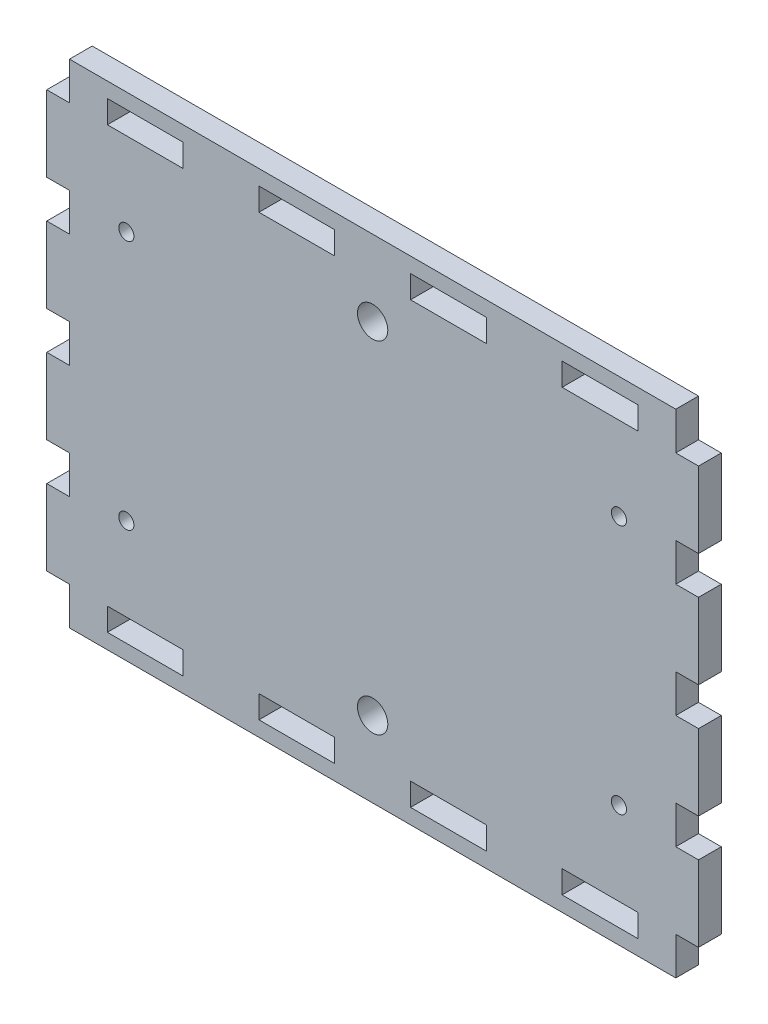
SolidWorks part; units mm, degrees
ref_plane "前视基准面" through (0, 0, 0) normal (0, 0, 1) x (1, 0, 0)
ref_plane "上视基准面" through (0, 0, 0) normal (0, 1, 0) x (1, 0, 0)
ref_plane "右视基准面" through (0, 0, 0) normal (1, 0, 0) x (0, 0, -1)
sketch "草图1" plane through (0, 0, 0) normal (0, 0, 1) x (1, 0, 0)
  line L0 (0, -55) -> (0, 55) construction
  line L1 (-32.5, 16.5) -> (32.5, 16.5) construction
  line L2 (-32.5, 16.5) -> (-32.5, -16.5) construction
  line L3 (-32.5, -16.5) -> (32.5, -16.5) construction
  line L4 (32.5, 16.5) -> (32.5, -16.5) construction
  line L5 (-32.5, 16.5) -> (32.5, -16.5) construction
  line L6 (-32.5, -16.5) -> (32.5, 16.5) construction
  line L7 (55, 0) -> (-55, 0) construction
  line L8 (-15, 27.5) -> (-15, 30.5)
  line L10 (-40, 17.5) -> (-40, 12.5)
  line L12 (40, 17.5) -> (40, 12.5)
  line L13 (-40, 27.5) -> (40, -27.5) construction
  line L14 (-40, -27.5) -> (40, 27.5) construction
  line L15 (-35, 27.5) -> (-25, 27.5)
  line L16 (-35, 27.5) -> (-35, 30.5)
  line L17 (-35, 30.5) -> (-25, 30.5)
  line L18 (-25, 27.5) -> (-25, 30.5)
  line L19 (-15, 27.5) -> (-5, 27.5)
  line L20 (-5, 27.5) -> (-5, 30.5)
  line L21 (-15, 30.5) -> (-5, 30.5)
  line L22 (5, 27.5) -> (5, 30.5)
  line L23 (5, 27.5) -> (15, 27.5)
  line L24 (15, 27.5) -> (15, 30.5)
  line L25 (5, 30.5) -> (15, 30.5)
  line L26 (25, 27.5) -> (25, 30.5)
  line L27 (25, 27.5) -> (35, 27.5)
  line L28 (35, 27.5) -> (35, 30.5)
  line L29 (25, 30.5) -> (35, 30.5)
  line L30 (-40, 27.5) -> (-40, 32.5)
  line L31 (-40, 32.5) -> (40, 32.5)
  line L32 (40, 32.5) -> (40, 27.5)
  line L33 (25, -27.5) -> (35, -27.5)
  line L34 (35, -27.5) -> (35, -30.5)
  line L35 (25, -30.5) -> (35, -30.5)
  line L36 (25, -27.5) -> (25, -30.5)
  line L37 (5, -27.5) -> (15, -27.5)
  line L38 (15, -27.5) -> (15, -30.5)
  line L39 (5, -30.5) -> (15, -30.5)
  line L40 (5, -27.5) -> (5, -30.5)
  line L41 (-15, -27.5) -> (-5, -27.5)
  line L42 (-5, -27.5) -> (-5, -30.5)
  line L43 (-15, -30.5) -> (-5, -30.5)
  line L44 (-15, -27.5) -> (-15, -30.5)
  line L45 (-35, -30.5) -> (-25, -30.5)
  line L46 (-25, -27.5) -> (-25, -30.5)
  line L47 (-35, -27.5) -> (-25, -27.5)
  line L48 (-35, -27.5) -> (-35, -30.5)
  line L49 (-40, -27.5) -> (-40, -32.5)
  line L50 (-40, -32.5) -> (40, -32.5)
  line L51 (40, -32.5) -> (40, -27.5)
  line L53 (40, 27.5) -> (43, 27.5)
  line L55 (40, 17.5) -> (43, 17.5)
  line L56 (43, 27.5) -> (43, 17.5)
  line L57 (40, 12.5) -> (43, 12.5)
  line L58 (43, 12.5) -> (43, 2.5)
  line L59 (40, 2.5) -> (43, 2.5)
  line L61 (40, -2.5) -> (43, -2.5)
  line L62 (43, -2.5) -> (43, -12.5)
  line L63 (40, -12.5) -> (43, -12.5)
  line L65 (40, -17.5) -> (43, -17.5)
  line L66 (43, -17.5) -> (43, -27.5)
  line L67 (40, -27.5) -> (43, -27.5)
  line L68 (-40, -17.5) -> (-43, -17.5)
  line L69 (-43, -17.5) -> (-43, -27.5)
  line L70 (-40, -27.5) -> (-43, -27.5)
  line L72 (-40, -2.5) -> (-43, -2.5)
  line L73 (-43, -2.5) -> (-43, -12.5)
  line L74 (-40, -12.5) -> (-43, -12.5)
  line L76 (-40, 12.5) -> (-43, 12.5)
  line L77 (-43, 12.5) -> (-43, 2.5)
  line L78 (-40, 2.5) -> (-43, 2.5)
  line L80 (-40, 17.5) -> (-43, 17.5)
  line L81 (-43, 27.5) -> (-43, 17.5)
  line L82 (-40, 27.5) -> (-43, 27.5)
  line L84 (-40, 2.5) -> (-40, -2.5)
  line L85 (-40, -12.5) -> (-40, -17.5)
  line L88 (40, -12.5) -> (40, -17.5)
  line L90 (40, 2.5) -> (40, -2.5)
  circle A0 centre (-32.5, 16.5) radius 1
  circle A1 centre (32.5, 16.5) radius 1
  circle A2 centre (-32.5, -16.5) radius 1
  circle A3 centre (32.5, -16.5) radius 1
  circle A4 centre (0, 22.5) radius 2
  circle A6 centre (0, -22.5) radius 2
  point P0 (0, 0)
  point P14 (0, 0)
  dimension "D3" = 2
  dimension "D6" = 4
  dimension "D1" = 65
  dimension "D2" = 33
  dimension "D4" = 80
  dimension "D5" = 55
  dimension "D7" = 6
  dimension "D8" = 10
  dimension "D9" = 3
  dimension "D10" = 5
  dimension "D12" = 3
  dimension "D13" = 10
  dimension "D15" = 45
  dimension "D11" = 4
  dimension "D14" = 4
extrude "凸台-拉伸1" add sketch "草图1" along normal blind 3
